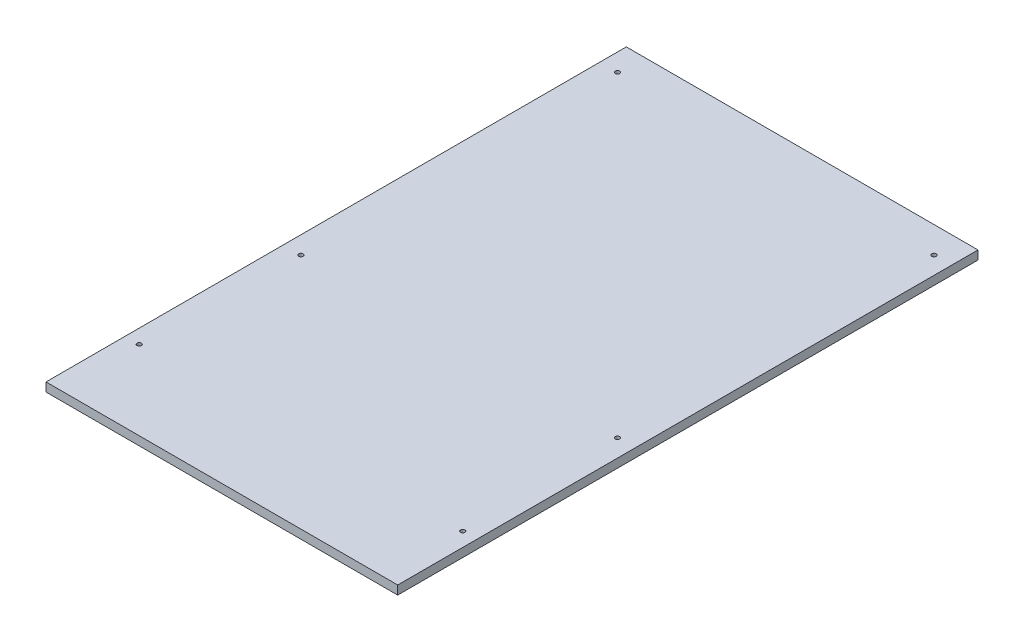
SolidWorks part; units mm, degrees
ref_plane "Piano frontale" through (0, 0, 0) normal (0, 0, 1) x (1, 0, 0)
ref_plane "Piano superiore" through (0, 0, 0) normal (0, 1, 0) x (1, 0, 0)
ref_plane "Piano destro" through (0, 0, 0) normal (1, 0, 0) x (0, 0, -1)
sketch "Schizzo1" plane through (0, 0, 0) normal (0, 1, 0) x (1, 0, 0)
  line L1 (-100, 0) -> (100, 0)
  line L2 (-100, 0) -> (-100, 330)
  line L3 (-100, 330) -> (100, 330)
  line L4 (100, 0) -> (100, 330)
  point P4 (0, 330)
  point P5 (0, 0)
  dimension "D1" = 200
  dimension "D2" = 330
extrude "Estrusione-Estrusione1" add sketch "Schizzo1" along normal blind 5
sketch "Schizzo2" plane through (0, 5, 0) normal (0, 1, 0) x (1, 0, 0)
  line L0 (0, 0) -> (0, 286.0309) construction
  line L1 (-100, 0) -> (100, 0) construction
  line L2 (-100, 330) -> (-100, 0) construction
  point P0 (-92, 45)
  point P1 (92, 45)
  point P2 (-90, 134.9778)
  point P3 (90, 134.9778)
  point P4 (-90, 314.9778)
  point P5 (90, 314.9778)
  dimension "D1" = 8
  dimension "D2" = 45
  dimension "D3" = 90
  dimension "D4" = 180
  dimension "D5" = 180
hole_wizard "Foro filettato M3-1" positions "Schizzo2" profile "Schizzo3" tap size "M3" standard "ISO" end condition through all
sketch "Schizzo3" plane through (-92, 5, -45) normal (1, 0, 0) x (0, 0, 1)
  line L0 (0, 0) -> (0, 5)
  line L1 (0, 5) -> (1.25, 5)
  line L2 (1.25, 5) -> (1.25, 0)
  line L5 (1.25, 0) -> (0, 0)
  line L11 (0, -6.35) -> (0, 107.95) construction
  dimension "Thru Tap Drill Dia." = 2.5
  dimension "Thru Tap Drill Depth" = 5
cosmetic thread "Filettatura del foro1"
cosmetic thread "Filettatura del foro2"
cosmetic thread "Filettatura del foro3"
cosmetic thread "Filettatura del foro4"
cosmetic thread "Filettatura del foro5"
cosmetic thread "Filettatura del foro6"
